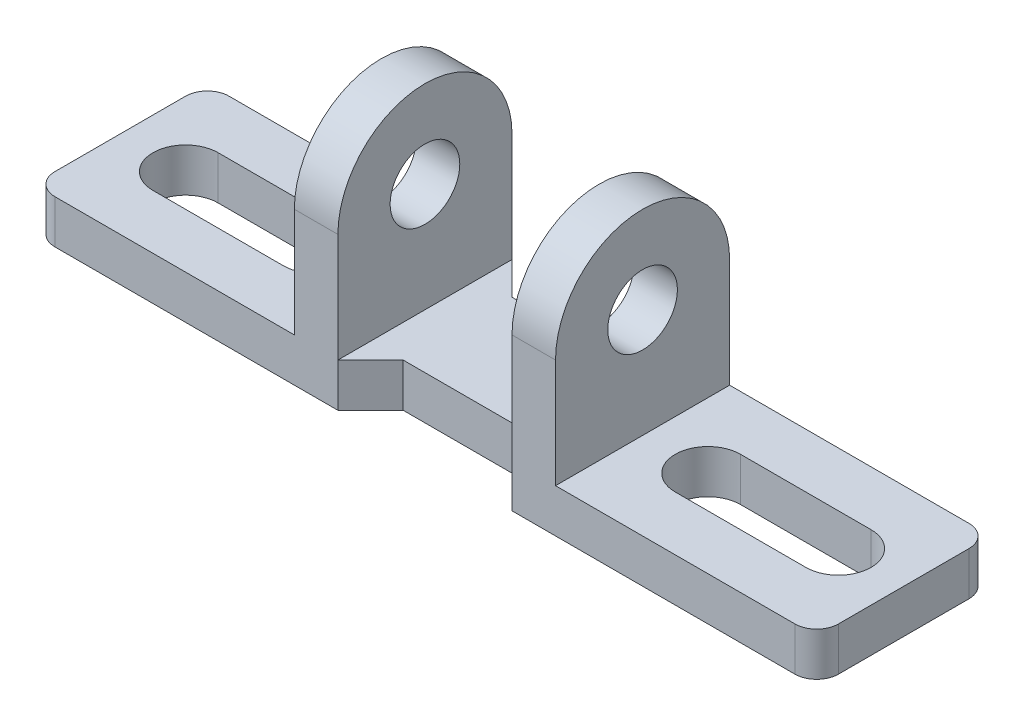
SolidWorks part; units mm, degrees
ref_plane "前视基准面" through (0, 0, 0) normal (0, 0, 1) x (1, 0, 0)
ref_plane "上视基准面" through (0, 0, 0) normal (0, 1, 0) x (1, 0, 0)
ref_plane "右视基准面" through (0, 0, 0) normal (1, 0, 0) x (0, 0, -1)
sketch "草图1" plane through (0, 0, 0) normal (0, 1, 0) x (1, 0, 0)
  line L0 (-15, 0) -> (-9, 0) construction
  line L7 (-18, 4) -> (18, 4)
  line L8 (-18, 4) -> (-18, -4)
  line L9 (-18, -4) -> (18, -4)
  line L10 (18, 4) -> (18, -4)
  line L11 (0, -4) -> (0, 4) construction
  line L12 (-18, 0) -> (18, 0) construction
  line L13 (-15, 1.5) -> (-9, 1.5)
  line L14 (-15, -1.5) -> (-9, -1.5)
  line L15 (9, 0) -> (15, 0) construction
  line L16 (9, 1.5) -> (15, 1.5)
  line L17 (9, -1.5) -> (15, -1.5)
  arc A2 (-15, 1.5) -> (-15, -1.5) centre (-15, 0) ccw
  arc A3 (-9, -1.5) -> (-9, 1.5) centre (-9, 0) ccw
  arc A4 (9, 1.5) -> (9, -1.5) centre (9, 0) ccw
  arc A5 (15, -1.5) -> (15, 1.5) centre (15, 0) ccw
  point P0 (0, 0)
  point P7 (-12, 0)
  point P14 (12, 0)
  dimension "D3" = 1.5
  dimension "D1" = 6
  dimension "D2" = 18
  dimension "D4" = 8
  dimension "D5" = 36
extrude "凸台-拉伸1" add sketch "草图1" along normal blind 2
sketch "草图2" plane through (0, 2, 0) normal (0, 1, 0) x (1, 0, 0)
  line L0 (0, -4) -> (0, 4) construction
  line L1 (-18, -4) -> (18, -4) construction
  line L2 (18, 4) -> (-18, 4) construction
  line L4 (-6, -4) -> (-4, -4)
  line L5 (-6, -4) -> (-6, 4)
  line L6 (-6, 4) -> (-4, 4)
  line L7 (-4, -4) -> (-4, 4)
  line L8 (4, 4) -> (6, 4)
  line L9 (4, 4) -> (4, -4)
  line L10 (4, -4) -> (6, -4)
  line L11 (6, 4) -> (6, -4)
  dimension "D1" = 2
  dimension "D2" = 8
extrude "凸台-拉伸2" add sketch "草图2" along normal blind 9
sketch "草图3" plane through (0, 2, 0) normal (0, 1, 0) x (1, 0, 0)
  line L0 (-4, 4) -> (-2.5, 2.5)
  line L1 (-2.5, 2.5) -> (2.5, 2.5)
  line L2 (2.5, 2.5) -> (4, 4)
  line L3 (-4, -4) -> (-2.5, -2.5)
  line L4 (-2.5, -2.5) -> (2.5, -2.5)
  line L5 (2.5, -2.5) -> (4, -4)
  line L6 (-4, -4) -> (4, -4) construction
  line L7 (4, 4) -> (4, -4) construction
  line L8 (4, 4) -> (-4, 4) construction
  line L9 (0, 0) -> (-2.7761, 0) construction
  line L14 (-4, -4) -> (4, -4)
  line L15 (4, -4) -> (4, 4)
  line L16 (4, 4) -> (-4, 4)
  line L17 (-4, 4) -> (-4, -4)
  line L18 (-4, -4) -> (4, -4)
  line L19 (4, -4) -> (4, 4)
  line L20 (4, 4) -> (-4, 4)
  line L21 (-4, 4) -> (-4, -4)
  line M9 (-4, -4) -> (4, -4)
  line M11 (4, 4) -> (-4, 4)
  dimension "D1" = 45
  dimension "D2" = 45
  dimension "D3" = 1.5
  dimension "D4" = 0
extrude "切除-拉伸1" cut sketch "草图3" against normal through all contours L5 L4 L3 M9 | L1 L2 L0 M11
sketch "草图4" plane through (6, 0, 0) normal (1, 0, 0) x (0, 0, -1)
  line L0 (-4, 11) -> (-4, 2) construction
  line L1 (4, 11) -> (4, 2) construction
  line L6 (-4, 2) -> (4, 2)
  line L7 (4, 2) -> (4, 11)
  line L8 (4, 11) -> (-4, 11)
  line L9 (-4, 11) -> (-4, 2)
  line L10 (-4, 2) -> (4, 2)
  line L11 (4, 2) -> (4, 11)
  line L12 (4, 11) -> (-4, 11)
  line L13 (-4, 11) -> (-4, 2)
  arc A0 (-4, 7) -> (4, 7) centre (0, 7) cw
  circle A1 centre (0, 7) radius 1.6
  line M8 (4, 11) -> (-4, 11)
  line M9 (-4, 11) -> (-4, 2)
  dimension "D1" = 3.2
  dimension "D2" = 4
  dimension "D3" = 0
extrude "切除-拉伸2" cut sketch "草图4" against normal through all contours A1 | A0 L12 M9 | A0 L11 M8
fillet "圆角1" radius 1 4 edges at (18, 1, -4) (18, 1, 4) (-18, 1, 4) (-18, 1, -4)
